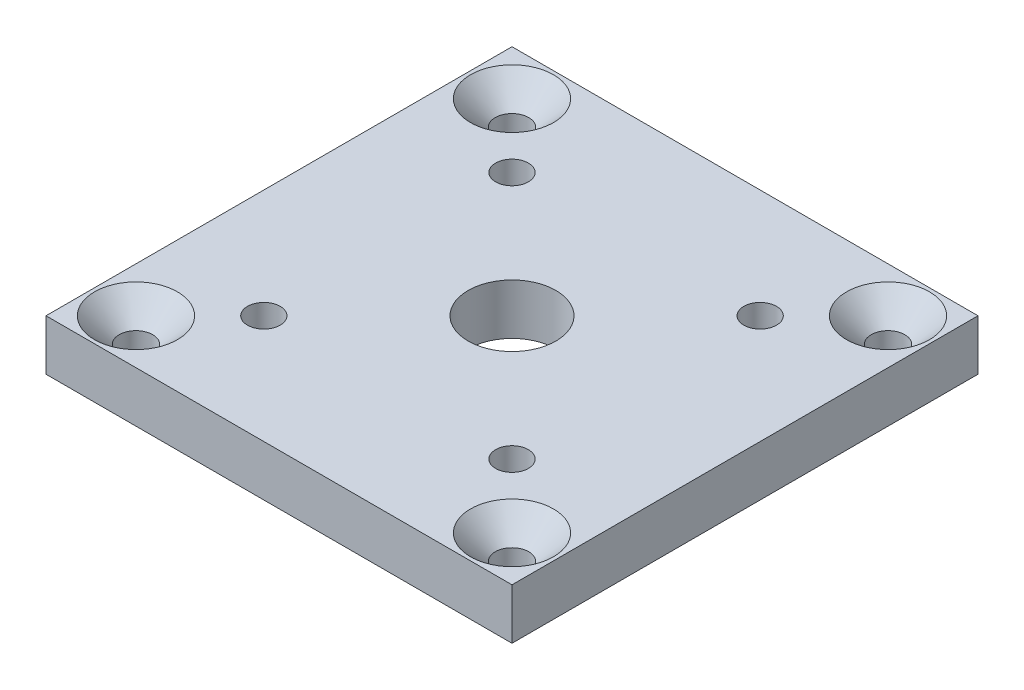
SolidWorks part; units mm, degrees
ref_plane "Top Plane" through (0, 0, 0) normal (0, 0, 1) x (1, 0, 0)
ref_plane "Front Plane" through (0, 0, 0) normal (0, 1, 0) x (1, 0, 0)
ref_plane "Right Plane" through (0, 0, 0) normal (1, 0, 0) x (0, 0, -1)
sketch "Sketch1" plane through (0, 0, 0) normal (0, 1, 0) x (1, 0, 0)
  line L0 (13.6537, 44.7663) -> (44.7663, 44.7663) construction
  line L1 (0, 0) -> (58.42, 0)
  line L2 (0, 0) -> (0, 58.42)
  line L3 (0, 58.42) -> (58.42, 58.42)
  line L4 (58.42, 0) -> (58.42, 58.42)
  line L5 (13.6537, 44.7663) -> (13.6537, 13.6537) construction
  line L6 (5.64, 52.78) -> (52.78, 52.78) construction
  line L7 (5.64, 52.78) -> (5.64, 5.64) construction
  line L8 (5.64, 5.64) -> (52.78, 5.64) construction
  line L9 (52.78, 52.78) -> (52.78, 5.64) construction
  line L10 (13.6537, 13.6537) -> (44.7663, 13.6537) construction
  line L11 (44.7663, 44.7663) -> (44.7663, 13.6537) construction
  line L12 (0, 58.42) -> (5.64, 52.78) construction
  line L13 (5.64, 52.78) -> (13.6537, 44.7663) construction
  line L14 (13.6537, 44.7663) -> (29.21, 29.21) construction
  line L15 (29.21, 29.21) -> (44.7663, 13.6537) construction
  line L16 (44.7663, 13.6537) -> (52.78, 5.64) construction
  line L17 (52.78, 5.64) -> (58.42, 0) construction
  circle A0 centre (5.64, 52.78) radius 2.1
  circle A1 centre (52.78, 52.78) radius 2.1
  circle A2 centre (52.78, 5.64) radius 2.1
  circle A3 centre (5.64, 5.64) radius 2.1
  circle A8 centre (29.21, 29.21) radius 5.5
  circle A9 centre (13.6537, 44.7663) radius 2.05
  circle A10 centre (44.7663, 44.7663) radius 2.05
  circle A11 centre (44.7663, 13.6537) radius 2.05
  circle A12 centre (13.6537, 13.6537) radius 2.05
  dimension "D1" = 58.42
  dimension "D4" = 4.2
  dimension "D5" = 11
  dimension "D6" = 4.1
  dimension "D2" = 47.14
  dimension "D3" = 44
extrude "Boss-Extrude1" add sketch "Sketch1" along normal blind 6.35
chamfer "Chamfer1" distance 2.48 angle 45 4 edges at (13.6537, 0, -42.7163) (44.7663, 0, -42.7163) (44.7663, 0, -11.6037) (13.6537, 0, -11.6037)
chamfer "Chamfer2" distance 3.1 angle 45 4 edges at (52.78, 6.35, -50.68) (52.78, 6.35, -3.54) (5.64, 6.35, -50.68) (5.64, 6.35, -3.54)
